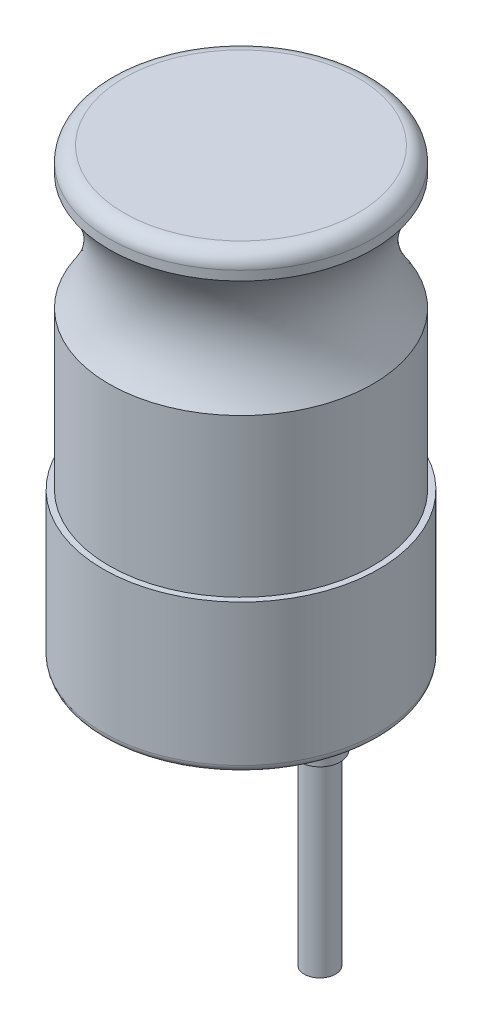
SolidWorks part; units mm, degrees
ref_plane "Front Plane" through (0, 0, 0) normal (0, 0, 1) x (1, 0, 0)
ref_plane "Top Plane" through (0, 0, 0) normal (0, 1, 0) x (1, 0, 0)
ref_plane "Right Plane" through (0, 0, 0) normal (1, 0, 0) x (0, 0, -1)
other "Center of Mass"
sketch "Sketch1" plane through (0, 0, 0) normal (0, 1, 0) x (1, 0, 0)
  circle A0 centre (0, 0) radius 18.5
  dimension "D1" = 37
extrude "Boss-Extrude1" add sketch "Sketch1" along normal blind 20
sketch "Sketch2" plane through (0, 20, 0) normal (0, 1, 0) x (1, 0, 0)
  circle A0 centre (0, 0) radius 17.7083
extrude "Boss-Extrude2" add sketch "Sketch2" along normal blind 40
sketch "Sketch3" plane through (0, 0, 0) normal (0, -1, 0) x (1, 0, 0)
  circle A0 centre (10.5837, 0) radius 2.0933
extrude "Boss-Extrude3" add sketch "Sketch3" along normal blind 30
sketch "Sketch4" plane through (0, 0, 0) normal (1, 0, 0) x (0, 0, -1)
  line L0 (-17.7083, 60) -> (-17.7083, 20) construction
  line L1 (-17.7083, 56.7534) -> (-17.7083, 41.1183)
  line L2 (0, 60) -> (0, 20) construction
  line L3 (17.7083, 60) -> (-17.7083, 60) construction
  line L4 (18.5, 20) -> (-18.5, 20) construction
  spline S0 degree 2 poles (-17.7083, 56.7534) (-12.0887, 49.2398) (-17.7083, 41.1183) knots 0 0 0 1 1 1
revolve "Cut-Revolve1" cut sketch "Sketch4" angle 360 about L2
fillet "Fillet1" radius 2 1 edges at (0, 60, 17.7083)
fillet "Fillet2" radius 1 1 edges at (0, 0, 18.5)
sketch "Sketch5" plane through (0, 0, 0) normal (0, -1, 0) x (1, 0, 0)
  circle A0 centre (10.5837, 0) radius 2.7487
extrude "Boss-Extrude4" add sketch "Sketch5" along normal blind 5
